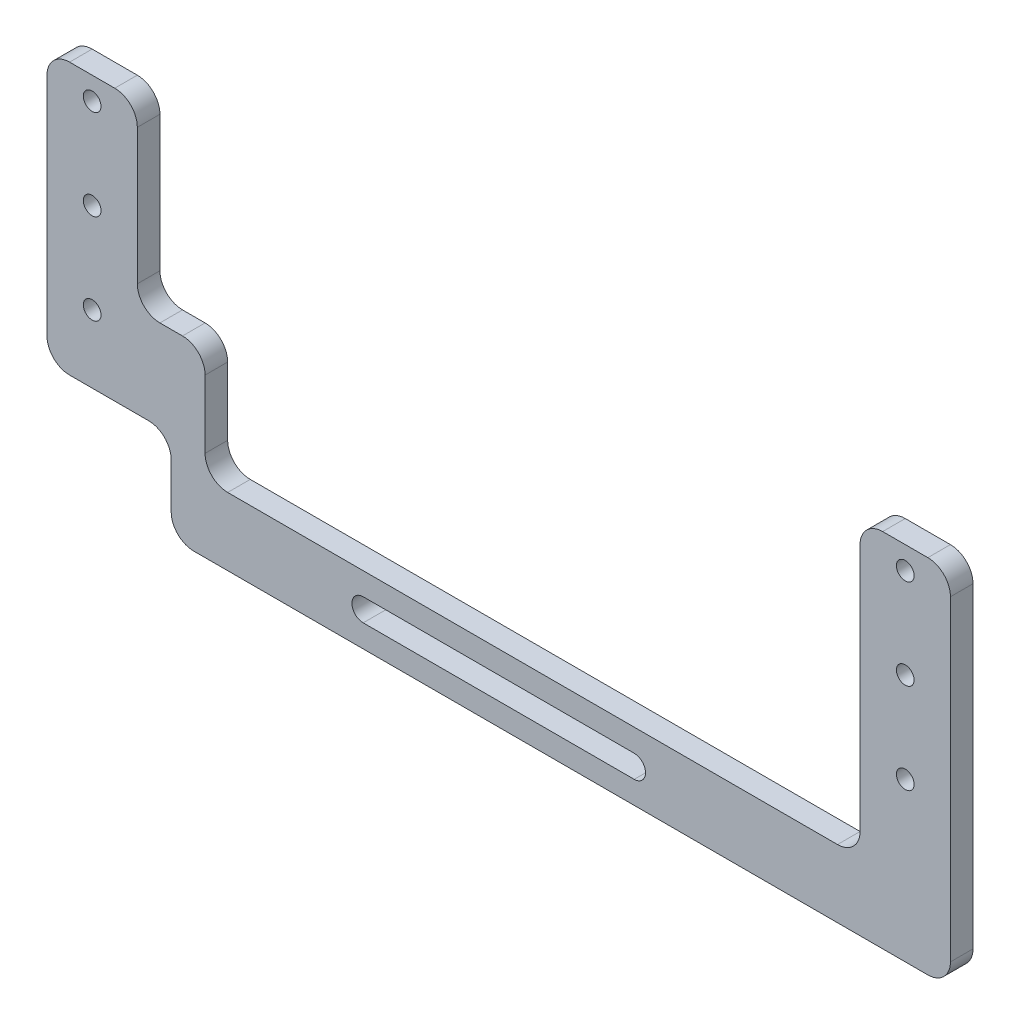
SolidWorks part; units mm, degrees
material "PC High Viscosity"
ref_plane "Front Plane" through (0, 0, 0) normal (0, 0, 1) x (1, 0, 0)
ref_plane "Top Plane" through (0, 0, 0) normal (0, 1, 0) x (1, 0, 0)
ref_plane "Right Plane" through (0, 0, 0) normal (1, 0, 0) x (0, 0, -1)
sketch "Sketch1" plane through (0, 0, 0) normal (0, 0, 1) x (1, 0, 0)
  line L13 (51.9148, 0) -> (77.3148, 0)
  line L14 (77.3148, 0) -> (77.3148, -101.6)
  line L15 (77.3148, -101.6) -> (-141.7602, -101.6)
  line L17 (51.9148, -101.6) -> (77.3148, -101.6)
  line L26 (-151.2852, -50.8) -> (-151.2852, 0)
  line L27 (-151.2852, 0) -> (-176.6852, 0)
  line L28 (-87.7852, -92.075) -> (-11.5852, -92.075) construction
  line L29 (-87.7852, -88.9) -> (-11.5852, -88.9)
  line L30 (-87.7852, -95.25) -> (-11.5852, -95.25)
  line L31 (-141.7602, -101.6) -> (77.3148, -101.6) construction
  line L33 (51.9148, -82.55) -> (51.9148, 0)
  line L35 (77.3148, 0) -> (-176.6852, 0) construction
  line L36 (-132.2352, -82.55) -> (-132.2352, -50.8)
  line L37 (-132.2352, -50.8) -> (-151.2852, -50.8)
  line L38 (-141.7602, -101.6) -> (-141.7602, -76.2)
  line L39 (-141.7602, -76.2) -> (-176.6852, -76.2)
  line L40 (-132.2352, -82.55) -> (51.9148, -82.55)
  line L41 (-176.6852, -76.2) -> (-176.6852, 0)
  line L43 (-151.2852, -337.8318) -> (-151.2852, 259.0682) construction
  arc A0 (-87.7852, -88.9) -> (-87.7852, -95.25) centre (-87.7852, -92.075) ccw
  arc A1 (-11.5852, -95.25) -> (-11.5852, -88.9) centre (-11.5852, -92.075) ccw
  point P0 (0, -11.412)
  point P1 (-49.6852, -92.075)
  dimension "D4" = 3.175
  dimension "D1" = 25.4
  dimension "D2" = 9.525
  dimension "D3" = 101.6
  dimension "D5" = 203.2
  dimension "D6" = 19.05
  dimension "D7" = 25.4
  dimension "D8" = 76.2
  dimension "D9" = 25.4
  dimension "D10" = 50.8
  dimension "D11" = 76.2
  dimension "D12" = 9.525
  dimension "D14" = 9.525
  dimension "D15" = 127
extrude "Boss-Extrude2" add sketch "Sketch1" along normal blind 6.35 contours L41 L39 L38 L15 L14 L13 L33 L40 L36 L37 L26 L27 A1 L30 A0 L29
fillet "Fillet1" radius 6.35 12 edges at (-176.6852, 0, 3.175) (-151.2852, 0, 3.175) (-151.2852, -50.8, 3.175) (-132.2352, -50.8, 3.175) (-132.2352, -82.55, 3.175) (51.9148, 0, 3.175) (77.3148, 0, 3.175) (-141.7602, -101.6, 3.175) (-141.7602, -76.2, 3.175) (-176.6852, -76.2, 3.175) (51.9148, -82.55, 3.175) (77.3148, -101.6, 3.175)
sketch "Sketch2" plane through (0, 0, 6.35) normal (0, 0, 1) x (1, 0, 0)
  line L0 (58.2648, 0) -> (70.9648, 0) construction
  line L1 (-157.6352, 0) -> (-170.3352, 0) construction
  circle A0 centre (64.6148, -6.35) radius 2.4892
  circle A1 centre (64.6148, -31.75) radius 2.4892
  circle A2 centre (64.6148, -57.15) radius 2.4892
  circle A3 centre (-163.9852, -6.35) radius 2.4892
  circle A4 centre (-163.9852, -31.75) radius 2.4892
  circle A5 centre (-163.9852, -57.15) radius 2.4892
  point P9 (64.6148, 0)
  point P14 (-163.9852, 0)
  dimension "D1" = 4.9784
  dimension "D5" = 4.9784
  dimension "D3" = 6.35
  dimension "D4" = 25.4
  dimension "D6" = 6.35
  dimension "D8" = 25.4
  dimension "D2" = 3
  dimension "D7" = 3
extrude "Cut-Extrude1" cut sketch "Sketch2" against normal through all
